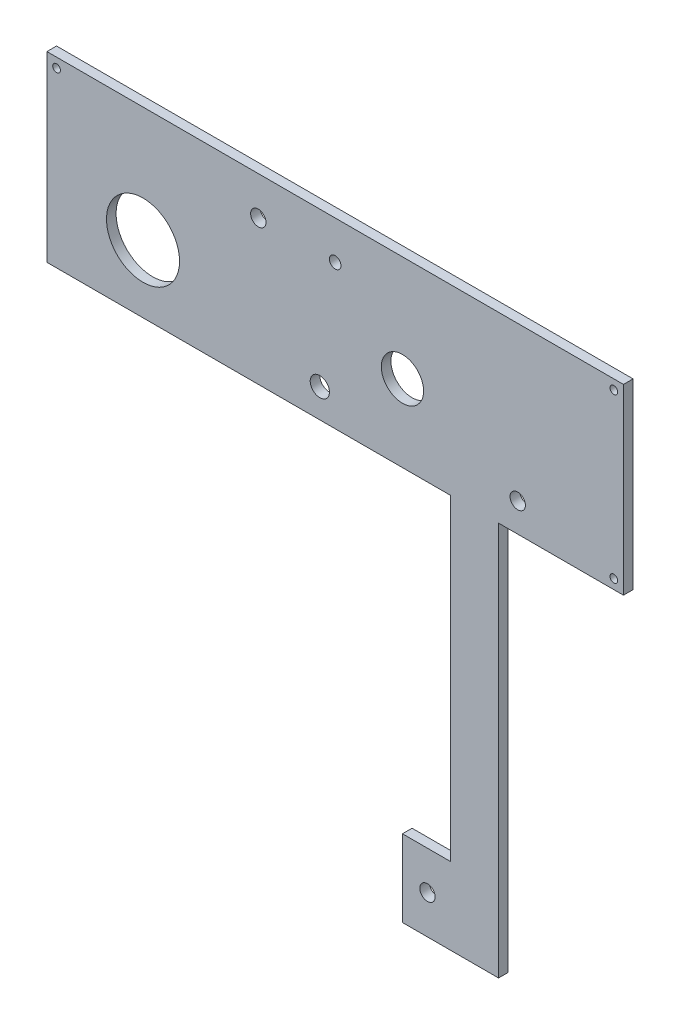
SolidWorks part; units mm, degrees
material "1060 Alloy"
ref_plane "Front Plane" through (0, 0, 0) normal (0, 0, 1) x (1, 0, 0)
ref_plane "Top Plane" through (0, 0, 0) normal (0, 1, 0) x (1, 0, 0)
ref_plane "Right Plane" through (0, 0, 0) normal (1, 0, 0) x (0, 0, -1)
sketch "Sketch1" plane through (0, 0, 0) normal (0, 0, 1) x (1, 0, 0)
  line L0 (105.4263, -213.2873) -> (55.4263, -213.2873)
  line L1 (170.4263, 86.7127) -> (170.4263, -8.2873)
  line L2 (170.4263, -8.2873) -> (105.4263, -8.2873)
  line L3 (105.4263, -8.2873) -> (105.4263, -213.2873)
  line L4 (80.4263, -8.2873) -> (-129.5737, -8.2873)
  line L5 (55.4263, -213.2873) -> (55.4263, -173.2873)
  line L7 (80.4263, -173.2873) -> (80.4263, -8.2873)
  line L9 (-129.5737, 86.7127) -> (170.4263, 86.7127)
  line L10 (92.9263, -279.3279) -> (92.9263, 250.3772) construction
  line L11 (-129.5737, -8.2873) -> (-129.5737, 86.7127)
  line L12 (55.4263, -173.2873) -> (80.4263, -173.2873)
  circle A0 centre (68.4263, -193.2873) radius 4
  circle A1 centre (115.4263, 6.7127) radius 4
  circle A2 centre (55.4263, 31.7127) radius 11
  circle A3 centre (-79.5737, 26.7127) radius 19
  circle A4 centre (12.4263, 6.7127) radius 5
  circle A5 centre (20.4263, 66.7127) radius 3
  circle A6 centre (-124.5737, 81.7127) radius 2
  circle A7 centre (165.4263, 81.7127) radius 2
  circle A8 centre (165.4263, -3.2873) radius 2
  circle A9 centre (-19.5737, 66.7127) radius 4
  dimension "D1" = 8
  dimension "D2" = 8
  dimension "D3" = 10
  dimension "D4" = 38
  dimension "D5" = 22
  dimension "D6" = 47
  dimension "D8" = 56
  dimension "D14" = 200
  dimension "D9" = 55
  dimension "D11" = 95
  dimension "D27" = 35
  dimension "D23" = 35
  dimension "D16" = 300
  dimension "D28" = 6
  dimension "D29" = 8
  dimension "D30" = 75
  dimension "D31" = 35
  dimension "D7" = 60
  dimension "D10" = 135
  dimension "D12" = 15
  dimension "D13" = 40
  dimension "D15" = 205
  dimension "D17" = 25
  dimension "D18" = 200
  dimension "D19" = 5
  dimension "D20" = 10
  dimension "D21" = 25
  dimension "D22" = 50
  dimension "D24" = 22.5
  dimension "D25" = 24.5
  dimension "D26" = 12.5
extrude "Extrude1" add sketch "Sketch1" along normal blind 5
